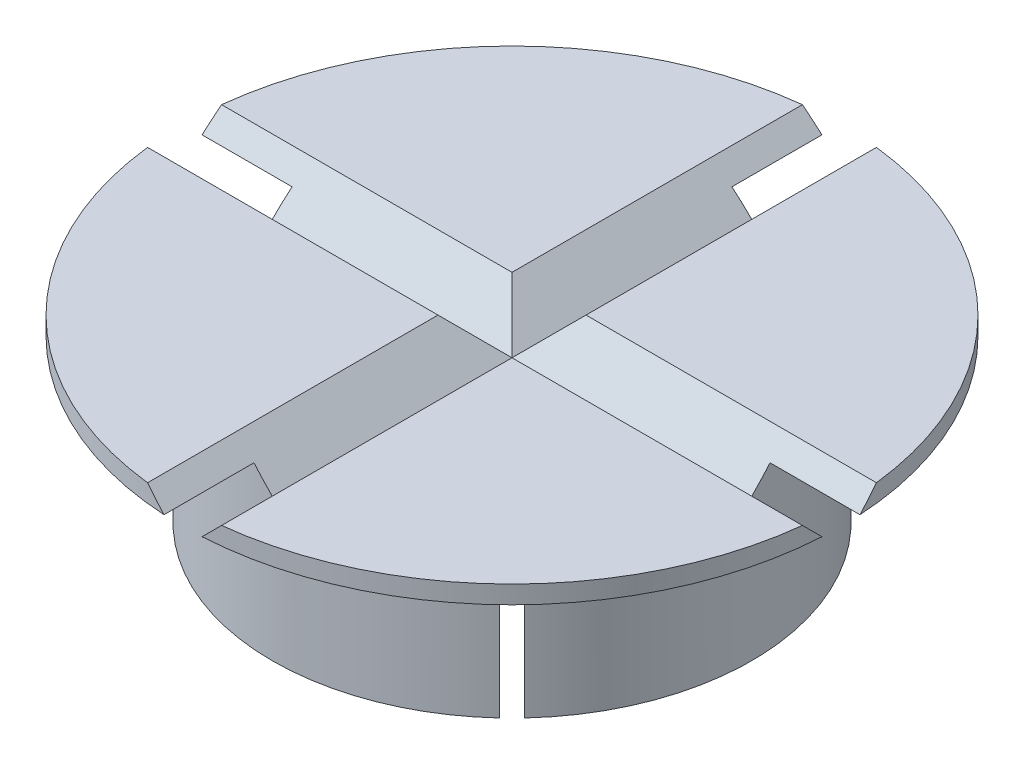
SolidWorks part; units mm, degrees
ref_plane "Front Plane" through (0, 0, 0) normal (0, 0, 1) x (1, 0, 0)
ref_plane "Top Plane" through (0, 0, 0) normal (0, 1, 0) x (1, 0, 0)
ref_plane "Right Plane" through (0, 0, 0) normal (1, 0, 0) x (0, 0, -1)
sketch "Sketch1" plane through (0, 0, 0) normal (1, 0, 0) x (0, 0, -1)
  line L0 (0, 0) -> (26.7, 0)
  line L1 (26.7, 0) -> (26.7, 18)
  line L2 (26.7, 18) -> (36.7, 18)
  line L3 (36.7, 18) -> (36.7, 20)
  line L4 (36.7, 20) -> (0, 20)
  line L5 (0, 20) -> (0, 0)
  dimension "D1" = 26.7
  dimension "D2" = 10
  dimension "D3" = 20
  dimension "D4" = 2
revolve "Revolve1" add sketch "Sketch1" angle 360 about L5
sketch "Sketch2" plane through (0, 0, 0) normal (0, 0, 1) x (1, 0, 0)
  line L0 (4.1213, 20) -> (0, 15.8787)
  line L1 (0, 15.8787) -> (-4.1213, 20)
  line L2 (-4.1213, 20) -> (4.1213, 20)
  line L3 (-2.1213, 18) -> (2.1213, 18) construction
  dimension "D1" = 20
  dimension "D2" = 18
  dimension "D3" = 3
extrude "Cut-Extrude1" cut sketch "Sketch2" against normal through all both and the other way through all
pattern_circular "CirPattern1" count 4 over 360 about axis through (0, 0, 0) along (0, 1, 0) of "Cut-Extrude1"
sketch "Sketch3" plane through (0, 0, 0) normal (0, -1, 0) x (1, 0, 0)
  circle A0 centre (0, 0) radius 23.75
  dimension "D1" = 47.5
extrude "Cut-Extrude2" cut sketch "Sketch3" against normal blind 12
sketch "Sketch4" plane through (0, 0, 0) normal (0, 1, 0) x (1, 0, 0)
  line L0 (-25.2341, -26.6483) -> (0, -1.4142)
  line L1 (0, 0) -> (0, -26.7) construction
  line L2 (-26.6483, -25.2341) -> (-1.4142, 0)
  line L3 (-26.7, 0) -> (0, 0) construction
  line L4 (-1.4142, 0) -> (0, -1.4142)
  arc A0 (-36.4679, -4.1213) -> (-4.1213, -36.4679) centre (0, 0) ccw construction
  arc A1 (-25.2341, -26.6483) -> (-26.6483, -25.2341) centre (0, 0) cw
  dimension "D1" = 2
  dimension "D2" = 45
extrude "Cut-Extrude3" cut sketch "Sketch4" along normal blind 12 contours L0 L4 L2 A1
pattern_circular "CirPattern2" count 4 over 360 about axis through (0, 0, 0) along (0, 1, 0) of "Cut-Extrude3"
